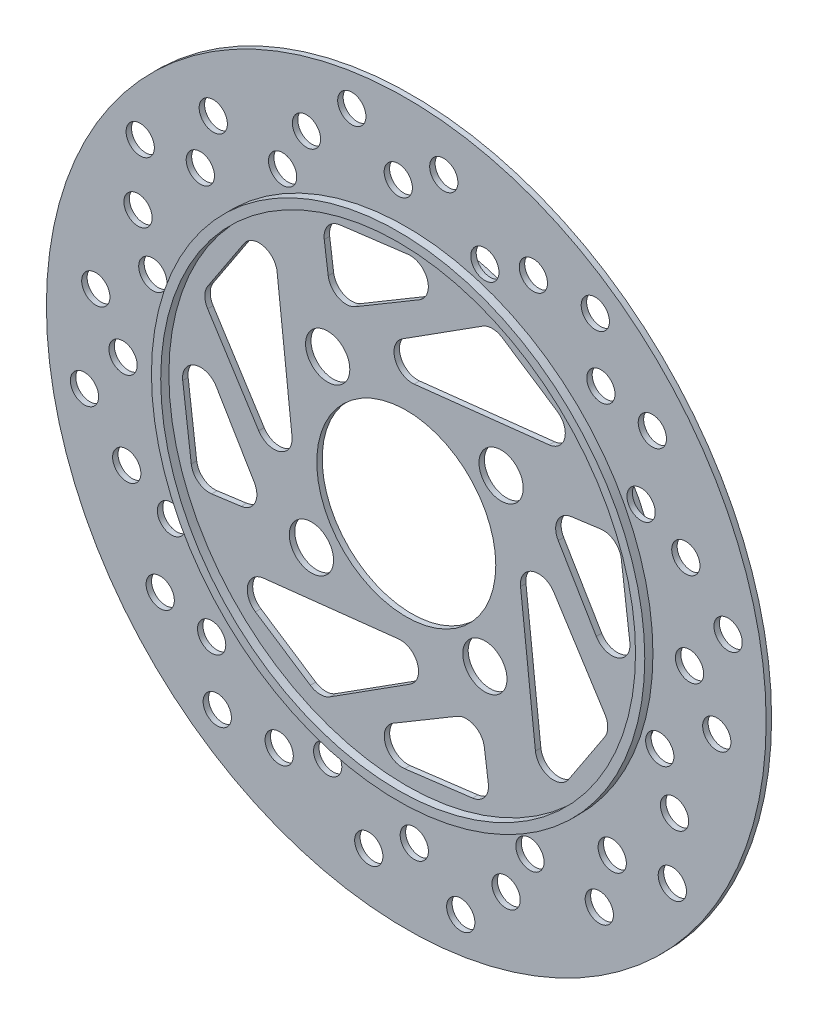
SolidWorks part; units mm, degrees
ref_plane "Front Plane" through (0, 0, 0) normal (0, 0, 1) x (1, 0, 0)
ref_plane "Top Plane" through (0, 0, 0) normal (0, 1, 0) x (1, 0, 0)
ref_plane "Right Plane" through (0, 0, 0) normal (1, 0, 0) x (0, 0, -1)
sketch "Sketch2" plane through (0, 0, 0) normal (0, 0, 1) x (1, 0, 0)
  line L0 (67.3333, 202) -> (336.6667, 202) construction
  line L1 (200.6986, 286.6879) -> (244.877, 314.8295)
  line L2 (255.7514, 314.7457) -> (285.9986, 294.817)
  line L3 (207.168, 268.314) -> (281.5937, 276.5269)
  line L4 (286.5965, 233.3486) -> (307.5625, 198.071)
  line L5 (293.8581, 248.3681) -> (310.115, 250.5577)
  line L6 (321.3718, 241.8942) -> (326.0808, 204.427)
  line L7 (312.2519, 152.4127) -> (292.3232, 122.1655)
  line L8 (265.8202, 200.9961) -> (274.033, 126.5705)
  line L9 (284.194, 207.4655) -> (312.3356, 163.2871)
  line L10 (230.8548, 121.5676) -> (195.5772, 100.6017)
  line L11 (239.4004, 86.7923) -> (201.9332, 82.0833)
  line L12 (245.8742, 114.306) -> (248.0639, 98.0491)
  line L13 (149.9189, 95.9122) -> (119.6717, 115.841)
  line L14 (198.5023, 142.344) -> (124.0767, 134.1311)
  line L15 (204.9717, 123.9701) -> (160.7933, 95.8285)
  line L16 (119.0738, 177.3094) -> (98.1078, 212.5869)
  line L17 (84.2985, 168.7637) -> (79.5895, 206.2309)
  line L18 (111.8122, 162.2899) -> (95.5553, 160.1003)
  line L19 (93.4184, 258.2452) -> (113.3472, 288.4925)
  line L20 (139.8501, 209.6619) -> (131.6373, 284.0875)
  line L21 (121.4763, 203.1925) -> (93.3347, 247.3709)
  line L22 (174.8155, 289.0904) -> (210.0931, 310.0563)
  line L23 (166.2699, 323.8656) -> (203.7371, 328.5747)
  line L24 (159.7961, 296.352) -> (157.6064, 312.6089)
  circle A0 centre (202.8352, 204.3373) radius 198.4042
  circle A1 centre (202.8352, 204.3373) radius 49.3437
  circle A12 centre (202.8352, 205.329) radius 135.9859
  circle A13 centre (31.6714, 226.0035) radius 7.7849
  circle A14 centre (46.6952, 200.9155) radius 7.7849
  circle A15 centre (48.7261, 150.3083) radius 7.7849
  circle A16 centre (73.3873, 137.1568) radius 7.7849
  circle A17 centre (25.4363, 175.2969) radius 7.7849
  circle A18 centre (89.3067, 312.6158) radius 7.7849
  circle A19 centre (96.4231, 340.9791) radius 7.7849
  circle A20 centre (56.1593, 309.5331) radius 7.7849
  circle A21 centre (54.9581, 275.3951) radius 7.7849
  circle A22 centre (63.0966, 248.6574) radius 7.7849
  circle A23 centre (198.4217, 361.469) radius 7.7849
  circle A24 centre (223.5096, 376.4928) radius 7.7849
  circle A25 centre (172.8031, 382.7279) radius 7.7849
  circle A26 centre (147.8145, 359.4381) radius 7.7849
  circle A27 centre (134.6629, 334.7769) radius 7.7849
  circle A28 centre (310.122, 318.8574) radius 7.7849
  circle A29 centre (338.4853, 311.741) radius 7.7849
  circle A30 centre (307.0392, 352.0048) radius 7.7849
  circle A31 centre (272.9012, 353.206) radius 7.7849
  circle A32 centre (246.1636, 345.0675) radius 7.7849
  circle A33 centre (358.9751, 209.7425) radius 7.7849
  circle A34 centre (373.9989, 184.6545) radius 7.7849
  circle A35 centre (380.234, 235.3611) radius 7.7849
  circle A36 centre (356.9442, 260.3496) radius 7.7849
  circle A37 centre (332.283, 273.5012) radius 7.7849
  circle A38 centre (316.3636, 98.0421) radius 7.7849
  circle A39 centre (309.2472, 69.6789) radius 7.7849
  circle A40 centre (349.511, 101.1249) radius 7.7849
  circle A41 centre (350.7122, 135.2629) radius 7.7849
  circle A42 centre (342.5737, 162.0006) radius 7.7849
  circle A43 centre (207.2486, 49.189) radius 7.7849
  circle A44 centre (182.1607, 34.1652) radius 7.7849
  circle A45 centre (232.8672, 27.9301) radius 7.7849
  circle A46 centre (257.8558, 51.2199) radius 7.7849
  circle A47 centre (271.0074, 75.8811) radius 7.7849
  circle A48 centre (95.5483, 91.8006) radius 7.7849
  circle A49 centre (67.185, 98.917) radius 7.7849
  circle A50 centre (98.6311, 58.6532) radius 7.7849
  circle A51 centre (132.7691, 57.452) radius 7.7849
  circle A52 centre (159.5067, 65.5905) radius 7.7849
  circle A53 centre (255.1122, 248.6574) radius 12.1962
  circle A54 centre (246.1636, 153.0519) radius 12.1962
  circle A55 centre (150.5581, 162.0006) radius 12.1962
  circle A56 centre (159.5067, 257.6061) radius 12.1962
  arc A57 (281.5937, 276.5269) -> (285.9986, 294.817) centre (280.4968, 286.4665) ccw
  arc A58 (200.6986, 286.6879) -> (207.168, 268.314) centre (206.0712, 278.2537) ccw
  arc A59 (255.7514, 314.7457) -> (244.877, 314.8295) centre (250.2496, 306.3953) ccw
  arc A60 (307.5625, 198.071) -> (326.0808, 204.427) centre (316.1589, 203.18) ccw
  arc A61 (321.3718, 241.8942) -> (310.115, 250.5577) centre (311.4499, 240.6472) ccw
  arc A62 (293.8581, 248.3681) -> (286.5965, 233.3486) centre (295.193, 238.4576) ccw
  arc A63 (312.2519, 152.4127) -> (312.3356, 163.2871) centre (303.9015, 157.9145) ccw
  arc A64 (274.033, 126.5705) -> (292.3232, 122.1655) centre (283.9727, 127.6673) ccw
  arc A65 (284.194, 207.4655) -> (265.8202, 200.9961) centre (275.7599, 202.093) ccw
  arc A66 (245.8742, 114.306) -> (230.8548, 121.5676) centre (235.9637, 112.9712) ccw
  arc A67 (195.5772, 100.6017) -> (201.9332, 82.0833) centre (200.6862, 92.0053) ccw
  arc A68 (239.4004, 86.7923) -> (248.0639, 98.0491) centre (238.1534, 96.7143) ccw
  arc A69 (149.9189, 95.9122) -> (160.7933, 95.8285) centre (155.4207, 104.2627) ccw
  arc A70 (124.0767, 134.1311) -> (119.6717, 115.841) centre (125.1735, 124.1914) ccw
  arc A71 (204.9717, 123.9701) -> (198.5023, 142.344) centre (199.5991, 132.4043) ccw
  arc A72 (111.8122, 162.2899) -> (119.0738, 177.3094) centre (110.4773, 172.2004) ccw
  arc A73 (98.1078, 212.5869) -> (79.5895, 206.2309) centre (89.5114, 207.478) ccw
  arc A74 (84.2985, 168.7637) -> (95.5553, 160.1003) centre (94.2204, 170.0108) ccw
  arc A75 (93.4184, 258.2452) -> (93.3347, 247.3709) centre (101.7689, 252.7434) ccw
  arc A76 (131.6373, 284.0875) -> (113.3472, 288.4925) centre (121.6976, 282.9907) ccw
  arc A77 (121.4763, 203.1925) -> (139.8501, 209.6619) centre (129.9105, 208.565) ccw
  arc A78 (159.7961, 296.352) -> (174.8155, 289.0904) centre (169.7066, 297.6868) ccw
  arc A79 (210.0931, 310.0563) -> (203.7371, 328.5747) centre (204.9841, 318.6527) ccw
  arc A80 (166.2699, 323.8656) -> (157.6064, 312.6089) centre (167.5169, 313.9437) ccw
  circle A81 centre (202.8352, 205.329) radius 130.8838
  point P9 (202.8352, 205.329)
  point P90 (202.8352, 205.329)
  point P98 (202.8352, 205.329)
  point P173 (202.8352, 205.329)
  dimension "D3" = 10
  dimension "D4" = 10
  dimension "D1" = 8
  dimension "D2" = 4
  dimension "D5" = 4
extrude "Boss-Extrude2" add sketch "Sketch2" against normal mid plane 3 contours A0 A52 A51 A50 A49 A48 A47 A46 A45 A44 A43 A42 A41 A40 A39 A38 A37 A36 A35 A34 A33 A32 A31 A30 A29 A28 | A81 L0 L17 A73 L16 A77 L21 A75 L19 A76 L20 A1 A65 L9 L4 A62 L5 A61 L6 A60 A80 L23 A79 L22 A78 L24 A59 L2 A57 L3 A58 L1 A56 A53 | L0 A81 A60 L4 L9 A63 L7 A64 L8 A65 A1 A77 L16 A72 L18 A74 L17 A54 A55 A68 L11 A67 L10 A66 L12 A71 L15 A69 L13 A70 L14
sketch "Sketch3" plane through (0, 0, 0) normal (0, 0, 1) x (1, 0, 0)
  circle A2 centre (202.8352, 205.329) radius 135.9859
  circle A3 centre (202.8352, 205.329) radius 130.8838
extrude "Boss-Extrude3" add sketch "Sketch3" along normal mid plane 12
scale "Scale1" bodies to scale 104 scale about centroid uniform scaling yes scale factor 0.55
